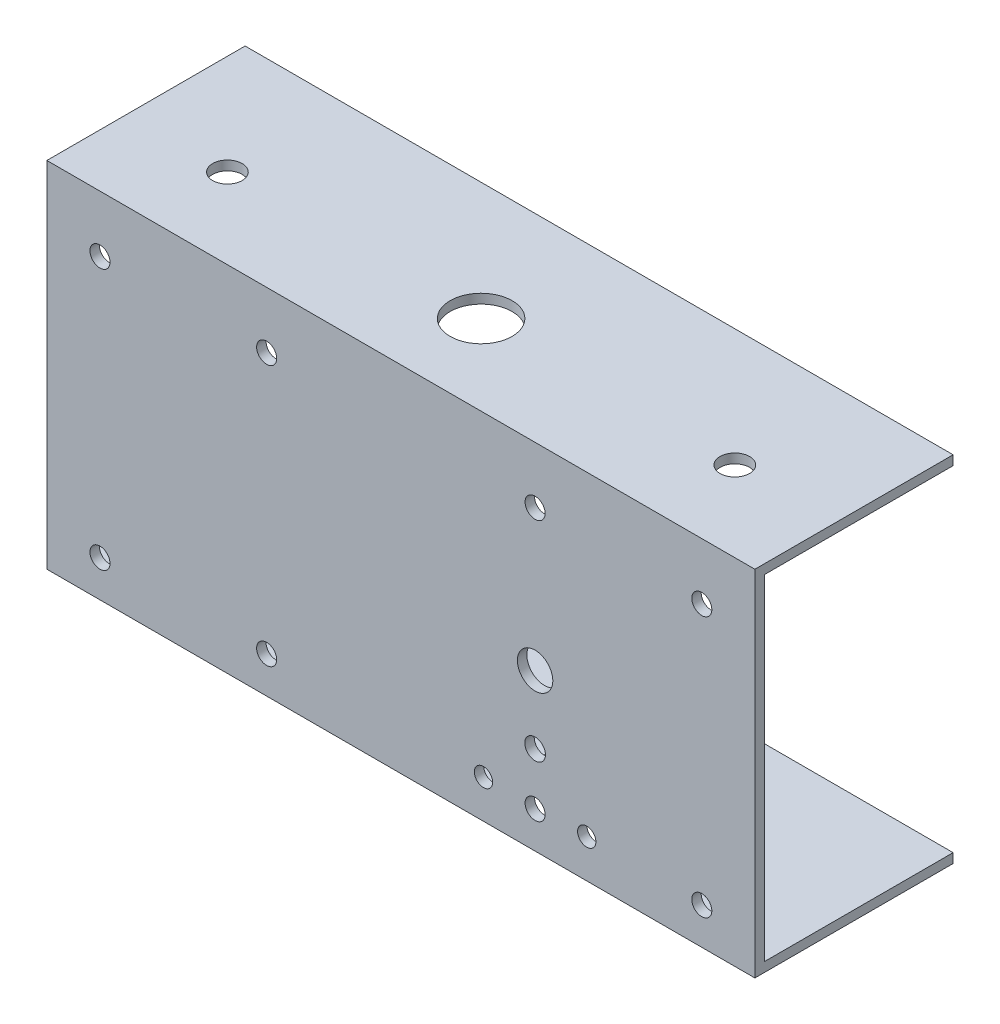
SolidWorks part; units mm, degrees
ref_plane "Front Plane" through (0, 0, 0) normal (0, 0, 1) x (1, 0, 0)
ref_plane "Top Plane" through (0, 0, 0) normal (0, 1, 0) x (1, 0, 0)
ref_plane "Right Plane" through (0, 0, 0) normal (1, 0, 0) x (0, 0, -1)
sketch "Sketch1" plane through (0, 0, 0) normal (0, 1, 0) x (1, 0, 0)
  line L0 (0, -17.6) -> (0, 17.6) construction
  line L13 (34.5, -12) -> (34.5, 13.5)
  line L15 (-60, -12) -> (-60, 20)
  line L16 (-60, 20) -> (60, 20)
  line L17 (60, -12) -> (60, 20)
  line L18 (34.5, 13.5) -> (11, 13.5)
  line L19 (11, 13.5) -> (11, -12)
  line L20 (60, -12) -> (34.5, -12)
  line L21 (11, -12) -> (-60, -12)
  circle A0 centre (0, 0) radius 5.25
  circle A1 centre (-43, 0) radius 2.5
  circle A2 centre (43, 0) radius 2.5
  point P0 (0, 0)
  dimension "D3" = 10.5
  dimension "D4" = 43
  dimension "D5" = 5
  dimension "D1" = 20
  dimension "D2" = 12
  dimension "D6" = 120
  dimension "D7" = 60
  dimension "D9" = 25.5
  dimension "D10" = 23.5
  dimension "D11" = 8.5
other "AlignGroup1"
other "AlignGroup2"
extrude "Boss-Extrude1" add sketch "Sketch1" along normal blind 1.6
sketch "Sketch3" plane through (0, 0, 0) normal (0, -1, 0) x (1, 0, 0)
  line L6 (60, 12) -> (-60, 12)
  line L7 (60, 12) -> (60, 13.6)
  line L8 (60, 13.6) -> (-60, 13.6)
  line L9 (-60, 12) -> (-60, 13.6)
  dimension "D1" = 1.6
extrude "Boss-Extrude3" add sketch "Sketch3" against normal blind 60
ref_plane "Plane1" through (0, 30, 0) normal (0, 1, 0) x (1, 0, 0)
mirror "Mirror1" about plane through (0, 30, 0) normal (0, 1, 0) of "Boss-Extrude1"
sketch "Sketch4" plane through (0, 0, 12) normal (0, 0, 1) x (1, 0, 0)
  line L2 (22.75, 26.5) -> (22.75, 5.2725)
  line L3 (60, 1.6) -> (-60, 1.6) construction
  line L5 (60, 58.4) -> (60, 1.6) construction
  circle A1 centre (22.75, 26.5) radius 3
  circle A5 centre (31.5, 6.5) radius 1.55
  circle A6 centre (14, 6.5) radius 1.55
  circle A7 centre (22.75, 15) radius 1.75
  dimension "D4" = 6
  dimension "D8" = 37.25
  dimension "D13" = 3.5
  dimension "D2" = 3.1
  dimension "D3" = 3.1
  dimension "D5" = 8.75
  dimension "D6" = 8.75
  dimension "D7" = 24.9
  dimension "D12" = 20
  dimension "D14" = 11.5
extrude "Cut-Extrude1" cut sketch "Sketch4" along normal blind 10
sketch "Sketch6" plane through (124.2445, 40.7, 12) normal (0, 0, 1) x (1, 0, 0)
  line L0 (-184.2445, -34.5) -> (-64.2445, -34.5)
  line L1 (-101.4945, -14.2) -> (-184.2445, -14.2)
  line L2 (-184.2445, 17.7) -> (-184.2445, -39.1) construction
  line L3 (-129.4945, -59.1) -> (-129.4945, -34.5)
  line L4 (-118.9945, -59.1) -> (-118.9945, -34.5)
  line L5 (-64.2445, 17.7) -> (-64.2445, -39.1) construction
  line L6 (-124.2445, -59.1) -> (-124.2445, -34.5)
  circle A8 centre (-146.9945, -34.5) radius 1.7
  circle A9 centre (-175.2445, -34.5) radius 1.7
  circle A10 centre (-73.2445, -34.5) radius 1.7
  circle A11 centre (-101.4945, -34.5) radius 1.7
  circle A12 centre (-73.2445, 9.7) radius 1.7
  circle A13 centre (-101.4945, 9.7) radius 1.7
  circle A14 centre (-146.9945, 9.7) radius 1.7
  circle A15 centre (-175.2445, 9.7) radius 1.7
  dimension "D3" = 54.75
  dimension "D6" = 44.2
  dimension "D7" = 3.4
  dimension "D8" = 9
  dimension "D9" = 3.4
  dimension "D11" = 3.4
  dimension "D4" = 3.4
  dimension "D5" = 3.4
  dimension "D14" = 3.4
  dimension "D2" = 54.75
  dimension "D10" = 20.3
  dimension "D12" = 17.5
  dimension "D13" = 17.5
extrude "Cut-Extrude2" cut sketch "Sketch6" along normal blind 25 contours A15 | A14 | A13 | A12 | A9 | A8 | A11 | A10
sketch "Sketch7" plane through (34.5, 0, 0) normal (-1, 0, 0) x (0, 0, 1)
  line L1 (12, 60) -> (-13.5, 60)
  line L2 (12, 60) -> (12, 58.4)
  line L3 (12, 58.4) -> (-13.5, 58.4)
  line L4 (-13.5, 60) -> (-13.5, 58.4)
extrude "Boss-Extrude4" add sketch "Sketch7" along normal blind 25
